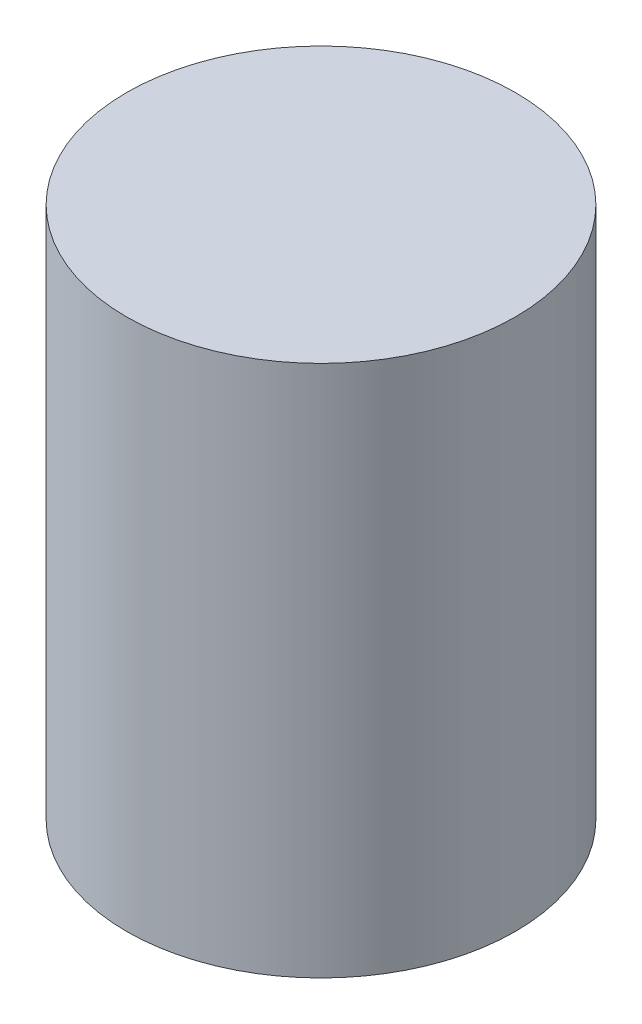
SolidWorks part; units mm, degrees
ref_plane "Płaszczyzna przednia" through (0, 0, 0) normal (0, 0, 1) x (1, 0, 0)
ref_plane "Płaszczyzna górna" through (0, 0, 0) normal (0, 1, 0) x (1, 0, 0)
ref_plane "Płaszczyzna prawa" through (0, 0, 0) normal (1, 0, 0) x (0, 0, -1)
sketch "Szkic1" plane through (0, 0, 0) normal (0, 1, 0) x (1, 0, 0)
  circle A0 centre (0, 0) radius 5.5
  dimension "D1" = 11
extrude "Dodanie-wyciągnięcie1" add sketch "Szkic1" along normal blind 15.06
